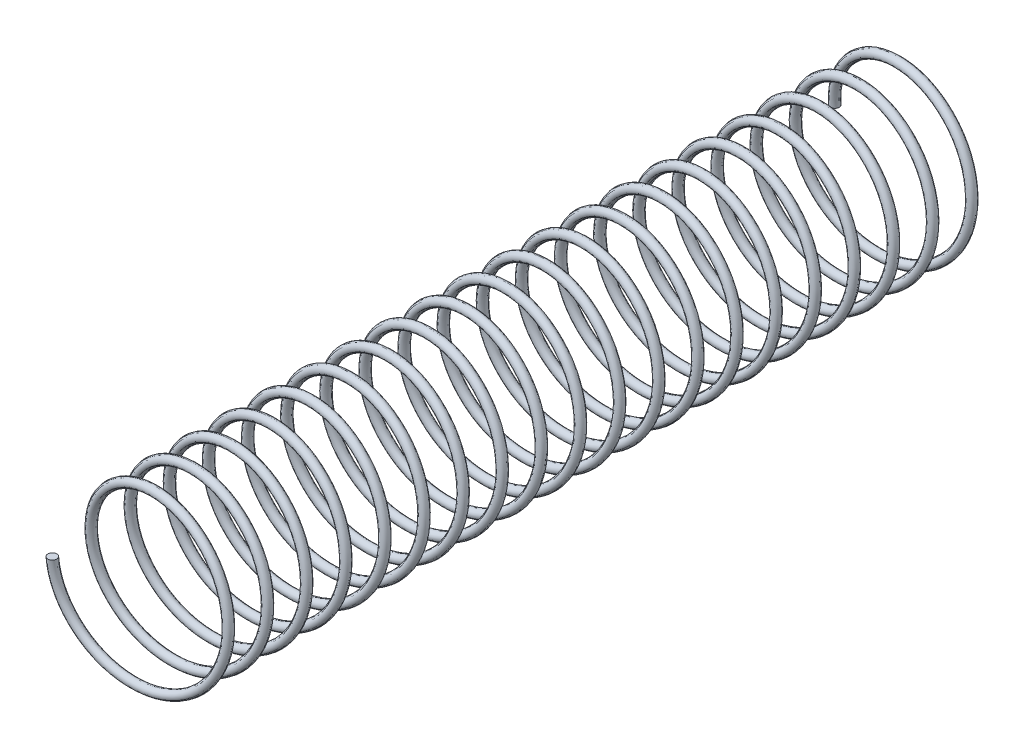
SolidWorks part; units mm, degrees
ref_plane "Front Plane" through (0, 0, 0) normal (0, 0, 1) x (1, 0, 0)
ref_plane "Top Plane" through (0, 0, 0) normal (0, 1, 0) x (1, 0, 0)
ref_plane "Right Plane" through (0, 0, 0) normal (1, 0, 0) x (0, 0, -1)
sketch "Sketch1" plane through (0, 0, 0) normal (0, 0, 1) x (1, 0, 0)
  circle A0 centre (0, 0) radius 2
  dimension "D1" = 4
curve "Helix/Spiral2" pitch 1 height 20 turns 20
sketch "Sketch8" plane through (0, 0, 0) normal (0, 1, 0) x (1, 0, 0)
  circle A0 centre (-1.9975, -19.9922) radius 0.1143
  spline S0 degree 3 poles (-2, 0) (-2, -0.0207) (-1.8959, -0.0626) (-1.451, -0.125) (-0.7853, -0.1875) (0, -0.25) (0.7853, -0.3125) (1.451, -0.375) (1.8959, -0.4375) (2.0521, -0.5) (1.8959, -0.5625) (1.451, -0.625) (0.5634, -0.7083) (-0.5634, -0.7917) (-1.451, -0.875) (-1.8959, -0.9375) (-2.0521, -1) (-1.8959, -1.0625) (-1.451, -1.125) (-0.5634, -1.2083) (0.5634, -1.2917) (1.451, -1.375) (1.8959, -1.4375) (2.0521, -1.5) (1.8959, -1.5625) (1.451, -1.625) (0.5634, -1.7083) (-0.5634, -1.7917) (-1.451, -1.875) (-1.8959, -1.9375) (-2.0521, -2) (-1.8959, -2.0625) (-1.451, -2.125) (-0.5634, -2.2083) (0.5634, -2.2917) (1.451, -2.375) (1.8959, -2.4375) (2.0521, -2.5) (1.8959, -2.5625) (1.451, -2.625) (0.5634, -2.7083) (-0.5634, -2.7917) (-1.451, -2.875) (-1.8959, -2.9375) (-2.0521, -3) (-1.8959, -3.0625) (-1.451, -3.125) (-0.5634, -3.2083) (0.5634, -3.2917) (1.451, -3.375) (1.8959, -3.4375) (2.0521, -3.5) (1.8959, -3.5625) (1.451, -3.625) (0.5634, -3.7083) (-0.5634, -3.7917) (-1.451, -3.875) (-1.8959, -3.9375) (-2.0521, -4) (-1.8959, -4.0625) (-1.451, -4.125) (-0.5634, -4.2083) (0.5634, -4.2917) (1.451, -4.375) (1.8959, -4.4375) (2.0521, -4.5) (1.8959, -4.5625) (1.451, -4.625) (0.5634, -4.7083) (-0.5634, -4.7917) (-1.451, -4.875) (-1.8959, -4.9375) (-2.0521, -5) (-1.8959, -5.0625) (-1.451, -5.125) (-0.5634, -5.2083) (0.5634, -5.2917) (1.451, -5.375) (1.8959, -5.4375) (2.0521, -5.5) (1.8959, -5.5625) (1.451, -5.625) (0.5634, -5.7083) (-0.5634, -5.7917) (-1.451, -5.875) (-1.8959, -5.9375) (-2.0521, -6) (-1.8959, -6.0625) (-1.451, -6.125) (-0.5634, -6.2083) (0.5634, -6.2917) (1.451, -6.375) (1.8959, -6.4375) (2.0521, -6.5) (1.8959, -6.5625) (1.451, -6.625) (0.5634, -6.7083) (-0.5634, -6.7917) (-1.451, -6.875) (-1.8959, -6.9375) (-2.0521, -7) (-1.8959, -7.0625) (-1.451, -7.125) (-0.5634, -7.2083) (0.5634, -7.2917) (1.451, -7.375) (1.8959, -7.4375) (2.0521, -7.5) (1.8959, -7.5625) (1.451, -7.625) (0.5634, -7.7083) (-0.5634, -7.7917) (-1.451, -7.875) (-1.8959, -7.9375) (-2.0521, -8) (-1.8959, -8.0625) (-1.451, -8.125) (-0.5634, -8.2083) (0.5634, -8.2917) (1.451, -8.375) (1.8959, -8.4375) (2.0521, -8.5) (1.8959, -8.5625) (1.451, -8.625) (0.5634, -8.7083) (-0.5634, -8.7917) (-1.451, -8.875) (-1.8959, -8.9375) (-2.0521, -9) (-1.8959, -9.0625) (-1.451, -9.125) (-0.5634, -9.2083) (0.5634, -9.2917) (1.451, -9.375) (1.8959, -9.4375) (2.0521, -9.5) (1.8959, -9.5625) (1.451, -9.625) (0.5634, -9.7083) (-0.5634, -9.7917) (-1.451, -9.875) (-1.8959, -9.9375) (-2.0521, -10) (-1.8959, -10.0625) (-1.451, -10.125) (-0.5634, -10.2083) (0.5634, -10.2917) (1.451, -10.375) (1.8959, -10.4375) (2.0521, -10.5) (1.8959, -10.5625) (1.451, -10.625) (0.5634, -10.7083) (-0.5634, -10.7917) (-1.451, -10.875) (-1.8959, -10.9375) (-2.0521, -11) (-1.8959, -11.0625) (-1.451, -11.125) (-0.5634, -11.2083) (0.5634, -11.2917) (1.451, -11.375) (1.8959, -11.4375) (2.0521, -11.5) (1.8959, -11.5625) (1.451, -11.625) (0.5634, -11.7083) (-0.5634, -11.7917) (-1.451, -11.875) (-1.8959, -11.9375) (-2.0521, -12) (-1.8959, -12.0625) (-1.451, -12.125) (-0.5634, -12.2083) (0.5634, -12.2917) (1.451, -12.375) (1.8959, -12.4375) (2.0521, -12.5) (1.8959, -12.5625) (1.451, -12.625) (0.5634, -12.7083) (-0.5634, -12.7917) (-1.451, -12.875) (-1.8959, -12.9375) (-2.0521, -13) (-1.8959, -13.0625) (-1.451, -13.125) (-0.5634, -13.2083) (0.5634, -13.2917) (1.451, -13.375) (1.8959, -13.4375) (2.0521, -13.5) (1.8959, -13.5625) (1.451, -13.625) (0.5634, -13.7083) (-0.5634, -13.7917) (-1.451, -13.875) (-1.8959, -13.9375) (-2.0521, -14) (-1.8959, -14.0625) (-1.451, -14.125) (-0.5634, -14.2083) (0.5634, -14.2917) (1.451, -14.375) (1.8959, -14.4375) (2.0521, -14.5) (1.8959, -14.5625) (1.451, -14.625) (0.5634, -14.7083) (-0.5634, -14.7917) (-1.451, -14.875) (-1.8959, -14.9375) (-2.0521, -15) (-1.8959, -15.0625) (-1.451, -15.125) (-0.5634, -15.2083) (0.5634, -15.2917) (1.451, -15.375) (1.8959, -15.4375) (2.0521, -15.5) (1.8959, -15.5625) (1.451, -15.625) (0.5634, -15.7083) (-0.5634, -15.7917) (-1.451, -15.875) (-1.8959, -15.9375) (-2.0521, -16) (-1.8959, -16.0625) (-1.451, -16.125) (-0.5634, -16.2083) (0.5634, -16.2917) (1.451, -16.375) (1.8959, -16.4375) (2.0521, -16.5) (1.8959, -16.5625) (1.451, -16.625) (0.5634, -16.7083) (-0.5634, -16.7917) (-1.451, -16.875) (-1.8959, -16.9375) (-2.0521, -17) (-1.8959, -17.0625) (-1.451, -17.125) (-0.5634, -17.2083) (0.5634, -17.2917) (1.451, -17.375) (1.8959, -17.4375) (2.0521, -17.5) (1.8959, -17.5625) (1.451, -17.625) (0.5634, -17.7083) (-0.5634, -17.7917) (-1.451, -17.875) (-1.8959, -17.9375) (-2.0521, -18) (-1.8959, -18.0625) (-1.451, -18.125) (-0.5634, -18.2083) (0.5634, -18.2917) (1.451, -18.375) (1.8959, -18.4375) (2.0521, -18.5) (1.8959, -18.5625) (1.451, -18.625) (0.5634, -18.7083) (-0.5634, -18.7917) (-1.451, -18.875) (-1.8959, -18.9375) (-2.0521, -19) (-1.8959, -19.0625) (-1.451, -19.125) (-0.5634, -19.2083) (0.5634, -19.2917) (1.451, -19.375) (1.8959, -19.4375) (2.0521, -19.5) (1.8959, -19.5625) (1.451, -19.625) (0.7853, -19.6875) (0, -19.75) (-0.7853, -19.8125) (-1.451, -19.875) (-1.8959, -19.9374) (-2, -19.9793) (-2, -20) knots 0 0 0 0 0.003125 0.00625 0.009375 0.0125 0.015625 0.01875 0.021875 0.025 0.028125 0.03125 0.034375 0.040625 0.04375 0.046875 0.05 0.053125 0.05625 0.059375 0.065625 0.06875 0.071875 0.075 0.078125 0.08125 0.084375 0.090625 0.09375 0.096875 0.1 0.103125 0.10625 0.109375 0.115625 0.11875 0.121875 0.125 0.128125 0.13125 0.134375 0.140625 0.14375 0.146875 0.15 0.153125 0.15625 0.159375 0.165625 0.16875 0.171875 0.175 0.178125 0.18125 0.184375 0.190625 0.19375 0.196875 0.2 0.203125 0.20625 0.209375 0.215625 0.21875 0.221875 0.225 0.228125 0.23125 0.234375 0.240625 0.24375 0.246875 0.25 0.253125 0.25625 0.259375 0.265625 0.26875 0.271875 0.275 0.278125 0.28125 0.284375 0.290625 0.29375 0.296875 0.3 0.303125 0.30625 0.309375 0.315625 0.31875 0.321875 0.325 0.328125 0.33125 0.334375 0.340625 0.34375 0.346875 0.35 0.353125 0.35625 0.359375 0.365625 0.36875 0.371875 0.375 0.378125 0.38125 0.384375 0.390625 0.39375 0.396875 0.4 0.403125 0.40625 0.409375 0.415625 0.41875 0.421875 0.425 0.428125 0.43125 0.434375 0.440625 0.44375 0.446875 0.45 0.453125 0.45625 0.459375 0.465625 0.46875 0.471875 0.475 0.478125 0.48125 0.484375 0.490625 0.49375 0.496875 0.5 0.503125 0.50625 0.509375 0.515625 0.51875 0.521875 0.525 0.528125 0.53125 0.534375 0.540625 0.54375 0.546875 0.55 0.553125 0.55625 0.559375 0.565625 0.56875 0.571875 0.575 0.578125 0.58125 0.584375 0.590625 0.59375 0.596875 0.6 0.603125 0.60625 0.609375 0.615625 0.61875 0.621875 0.625 0.628125 0.63125 0.634375 0.640625 0.64375 0.646875 0.65 0.653125 0.65625 0.659375 0.665625 0.66875 0.671875 0.675 0.678125 0.68125 0.684375 0.690625 0.69375 0.696875 0.7 0.703125 0.70625 0.709375 0.715625 0.71875 0.721875 0.725 0.728125 0.73125 0.734375 0.740625 0.74375 0.746875 0.75 0.753125 0.75625 0.759375 0.765625 0.76875 0.771875 0.775 0.778125 0.78125 0.784375 0.790625 0.79375 0.796875 0.8 0.803125 0.80625 0.809375 0.815625 0.81875 0.821875 0.825 0.828125 0.83125 0.834375 0.840625 0.84375 0.846875 0.85 0.853125 0.85625 0.859375 0.865625 0.86875 0.871875 0.875 0.878125 0.88125 0.884375 0.890625 0.89375 0.896875 0.9 0.903125 0.90625 0.909375 0.915625 0.91875 0.921875 0.925 0.928125 0.93125 0.934375 0.940625 0.94375 0.946875 0.95 0.953125 0.95625 0.959375 0.965625 0.96875 0.971875 0.975 0.978125 0.98125 0.984375 0.9875 0.990625 0.99375 0.996875 1 1 1 1 construction
sweep "Sweep1" add profiles "Sketch8" path "Helix/Spiral2"
